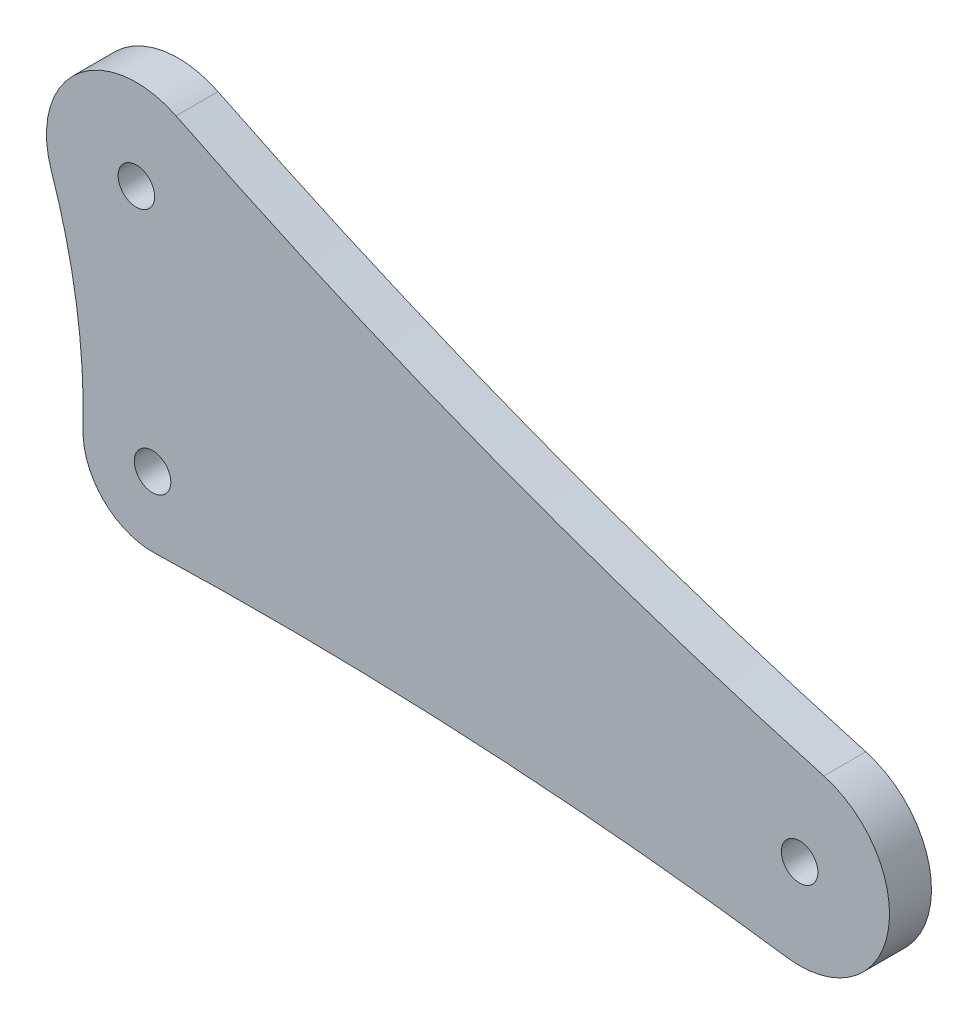
SolidWorks part; units mm, degrees
material "Balsa"
ref_plane "Front Plane" through (0, 0, 0) normal (0, 0, 1) x (1, 0, 0)
ref_plane "Top Plane" through (0, 0, 0) normal (0, 1, 0) x (1, 0, 0)
ref_plane "Right Plane" through (0, 0, 0) normal (1, 0, 0) x (0, 0, -1)
sketch "Sketch1" plane through (0, 0, 0) normal (0, 0, 1) x (1, 0, 0)
  line L0 (0, 0) -> (53.9865, -1.2074) construction
  line L1 (0, 0) -> (-1.35, 19.9544) construction
  line L2 (0, 0) -> (6.5815, 0) construction
  circle A0 centre (-1.35, 19.9544) radius 1.525
  circle A1 centre (0, 0) radius 1.525
  circle A2 centre (53.9865, -1.2074) radius 1.525
  arc A3 (-5.7981, 0.1479) -> (0.1755, -5.7973) centre (0, 0) ccw
  arc A4 (1.9611, 26.6839) -> (-8.4498, 17.5372) centre (-1.35, 19.9544) ccw
  arc A5 (52.9567, -8.6364) -> (56.0107, 6.0143) centre (53.9865, -1.2074) ccw
  arc A6 (-8.4498, 17.5372) -> (-5.7981, 0.1479) centre (-55.7819, 1.4227) cw
  arc A7 (1.9611, 26.6839) -> (56.0107, 6.0143) centre (141.0257, 309.3251) ccw
  arc A8 (52.9567, -8.6364) -> (0.1755, -5.7973) centre (9.7068, -320.6531) ccw
  dimension "D5" = 3.05
  dimension "D6" = 11.6
  dimension "D7" = 15
  dimension "D8" = 50
  dimension "D9" = 315
  dimension "D10" = 315
  dimension "D2" = 1.35
  dimension "D3" = 20
  dimension "D4" = 54
  dimension "D11" = 1.281
extrude "Boss-Extrude1" add sketch "Sketch1" along normal blind 3.5
